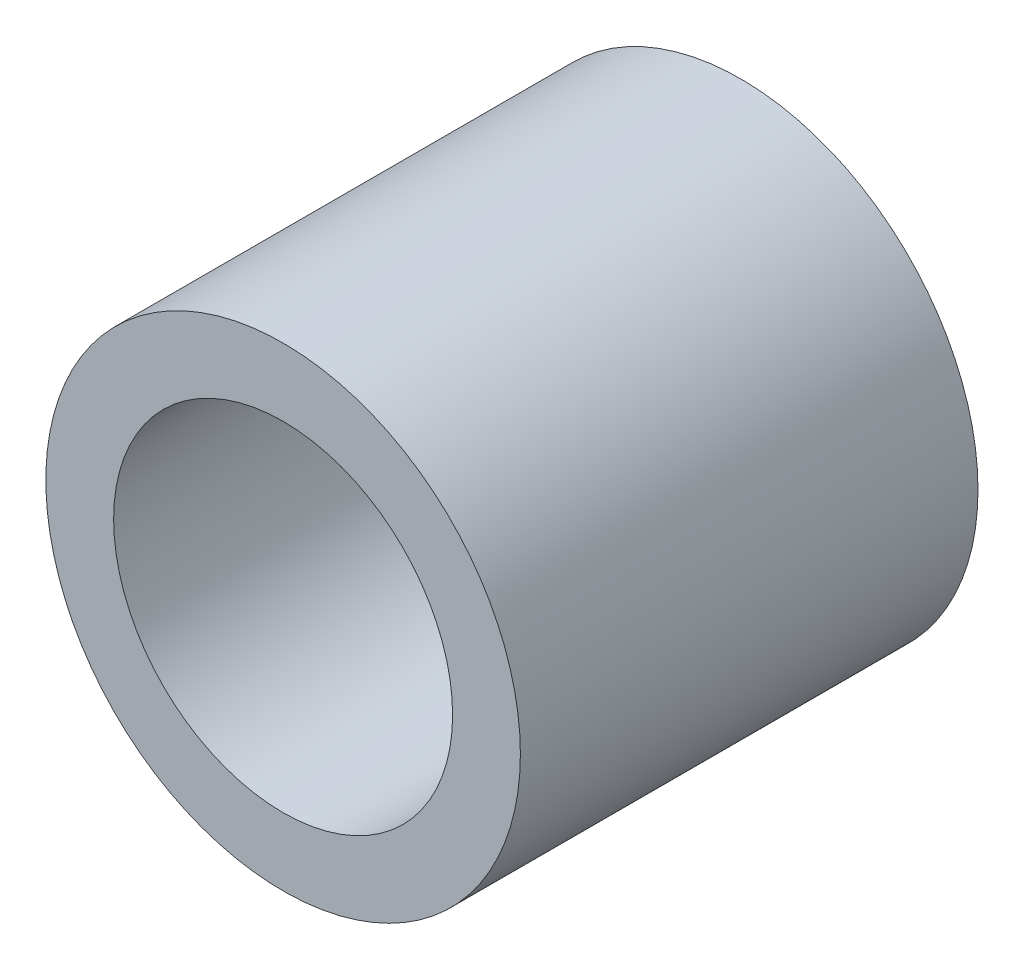
SolidWorks part; units mm, degrees
material "Gray Cast Iron"
ref_plane "Front Plane" through (0, 0, 0) normal (0, 0, 1) x (1, 0, 0)
ref_plane "Top Plane" through (0, 0, 0) normal (0, 1, 0) x (1, 0, 0)
ref_plane "Right Plane" through (0, 0, 0) normal (1, 0, 0) x (0, 0, -1)
sketch "Sketch1" plane through (0, 0, 0) normal (0, 0, 1) x (1, 0, 0)
  circle A0 centre (0, 0) radius 2.5
  circle A1 centre (0, 0) radius 3.5
  dimension "D1" = 7
  dimension "D2" = 5
extrude "Boss-Extrude1" add sketch "Sketch1" along normal blind 6.75
